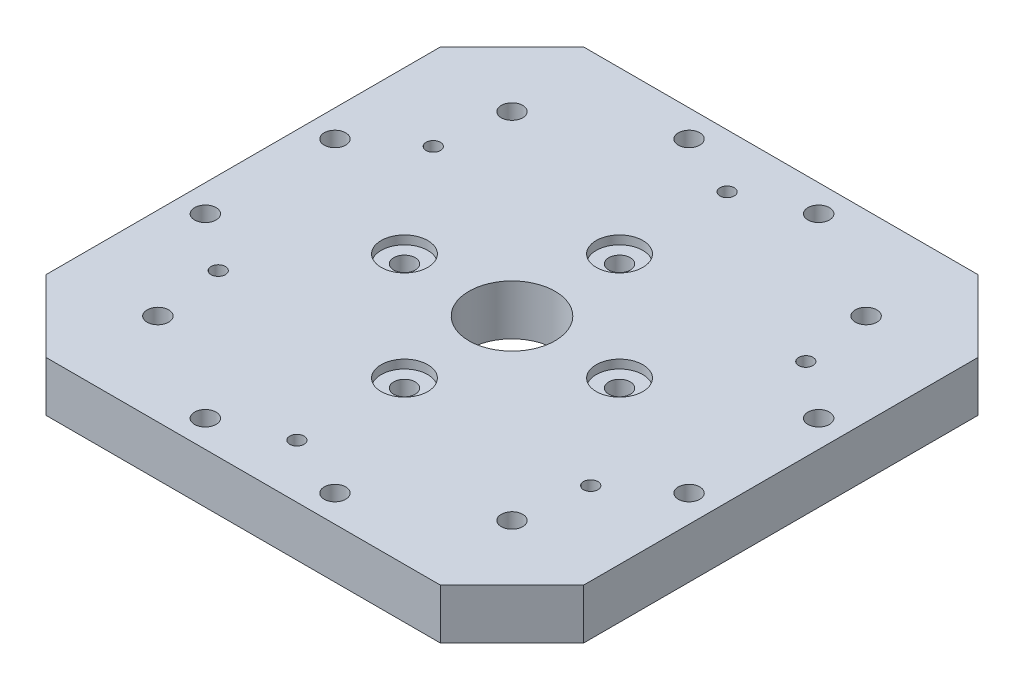
SolidWorks part; units mm, degrees
ref_plane "Front Plane" through (0, 0, 0) normal (0, 0, 1) x (1, 0, 0)
ref_plane "Top Plane" through (0, 0, 0) normal (0, 1, 0) x (1, 0, 0)
ref_plane "Right Plane" through (0, 0, 0) normal (1, 0, 0) x (0, 0, -1)
sketch "Sketch1" plane through (0, 0, 0) normal (0, 1, 0) x (1, 0, 0)
  line L0 (-49.4318, 0) -> (0, 0) construction
  line L1 (0, 0) -> (-47.2333, -12.6561) construction
  line L2 (-37.5, 37.5) -> (37.5, 37.5)
  line L3 (-37.5, 37.5) -> (-37.5, -37.5)
  line L4 (37.5, 37.5) -> (37.5, -37.5)
  line L5 (-37.5, -37.5) -> (37.5, -37.5)
  circle A0 centre (0, 0) radius 37.5 construction
  circle A1 centre (0, 0) radius 30 construction
  circle A2 centre (0, 0) radius 6
  circle A3 centre (0, 0) radius 15 construction
  circle A4 centre (0, 15) radius 1.5
  circle A5 centre (15, 0) radius 1.5
  circle A6 centre (0, -15) radius 1.5
  circle A7 centre (-15, 0) radius 1.5
  circle A11 centre (0, 0) radius 35 construction
  circle A12 centre (-33.737, -9.0398) radius 1.5
  circle A13 centre (-33.737, 9.0398) radius 1.5
  circle A14 centre (-24.6972, 24.6972) radius 1.5
  circle A15 centre (-9.0398, 33.737) radius 1.5
  circle A16 centre (9.0398, 33.737) radius 1.5
  circle A17 centre (24.6972, 24.6972) radius 1.5
  circle A18 centre (33.737, 9.0398) radius 1.5
  circle A19 centre (33.737, -9.0398) radius 1.5
  circle A20 centre (24.6972, -24.6972) radius 1.5
  circle A21 centre (9.0398, -33.737) radius 1.5
  circle A22 centre (-9.0398, -33.737) radius 1.5
  circle A23 centre (-24.6972, -24.6972) radius 1.5
  circle A24 centre (0, 30) radius 1
  circle A25 centre (25.9808, 15) radius 1
  circle A26 centre (25.9808, -15) radius 1
  circle A27 centre (0, -30) radius 1
  circle A28 centre (-25.9808, -15) radius 1
  circle A29 centre (-25.9808, 15) radius 1
  point P17 (0, 0)
  point P44 (0, 0)
  point P57 (0, 0)
  dimension "D1" = 75
  dimension "D2" = 60
  dimension "D3" = 12
  dimension "D4" = 3
  dimension "D6" = 30
  dimension "D7" = 70
  dimension "D9" = 3
  dimension "D11" = 2
  dimension "D8" = 15
  dimension "D5" = 4
  dimension "D10" = 12
  dimension "D12" = 6
extrude "Boss-Extrude1" add sketch "Sketch1" along normal blind 7
sketch "Sketch2" plane through (0, 7, 0) normal (0, 1, 0) x (1, 0, 0)
  circle A0 centre (0, 0) radius 15 construction
  circle A1 centre (0, 15) radius 3.25
  circle A2 centre (15, 0) radius 3.25
  circle A3 centre (0, -15) radius 3.25
  circle A4 centre (-15, 0) radius 3.25
  point P15 (0, 0)
  dimension "D1" = 6.5
  dimension "D2" = 4
extrude "Cut-Extrude1" cut sketch "Sketch2" against normal blind 1.2
chamfer "Chamfer1" distance 10 angle 45 4 edges at (-37.5, 3.5, -37.5) (37.5, 3.5, -37.5) (37.5, 3.5, 37.5) (-37.5, 3.5, 37.5)
